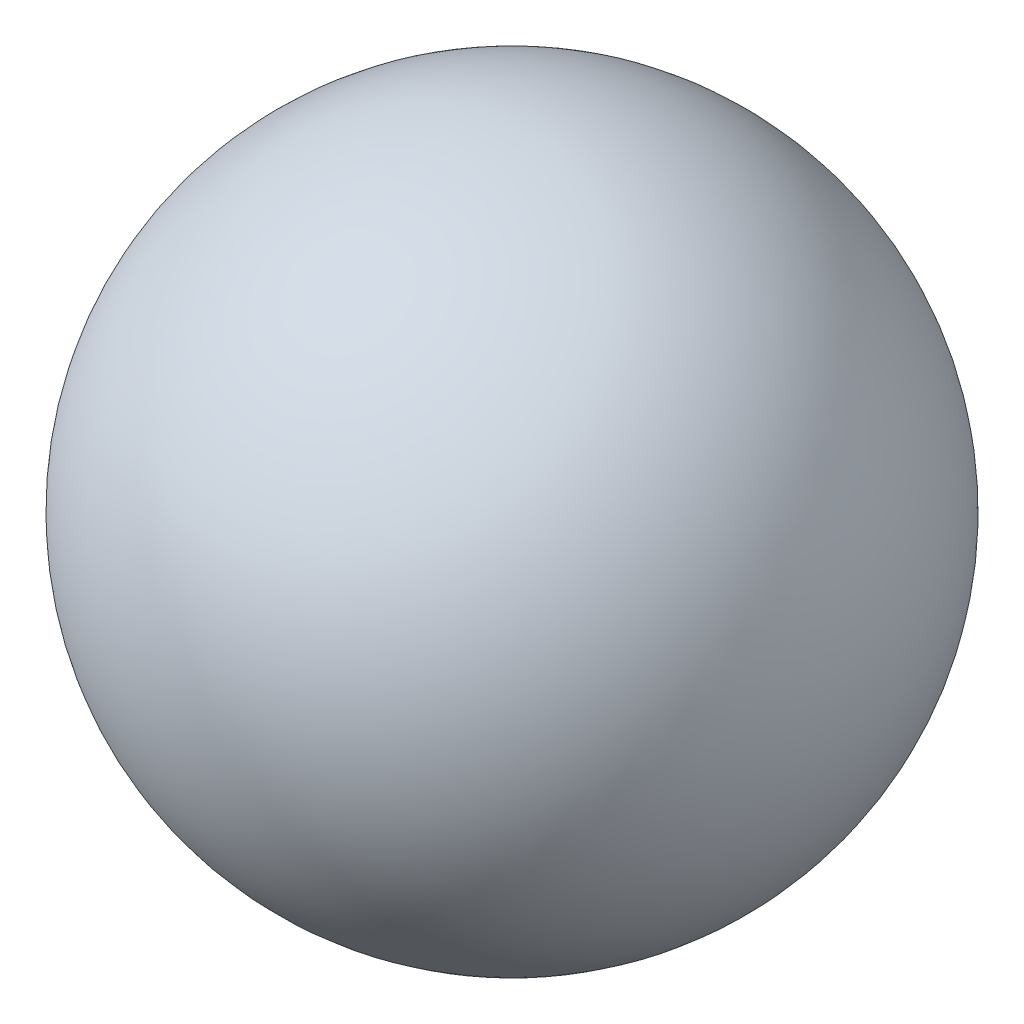
SolidWorks part; units mm, degrees
ref_plane "Front Plane" through (0, 0, 0) normal (0, 0, 1) x (1, 0, 0)
ref_plane "Top Plane" through (0, 0, 0) normal (0, 1, 0) x (1, 0, 0)
ref_plane "Right Plane" through (0, 0, 0) normal (1, 0, 0) x (0, 0, -1)
sketch "Sketch1" plane through (0, 0, 0) normal (0, 0, 1) x (1, 0, 0)
  line L0 (0, 6.4) -> (0, -6.4)
  arc A0 (0, -6.4) -> (0, 6.4) centre (0, 0) ccw
  dimension "D1" = 12.8
revolve "Revolve1" add sketch "Sketch1" angle 360 about L0
sketch "Sketch2" plane through (0, 0, 0) normal (0, 1, 0) x (1, 0, 0)
  circle A0 centre (0, 0) radius 2
  dimension "D1" = 4
extrude "Cut-Extrude1" cut sketch "Sketch2" against normal through all
